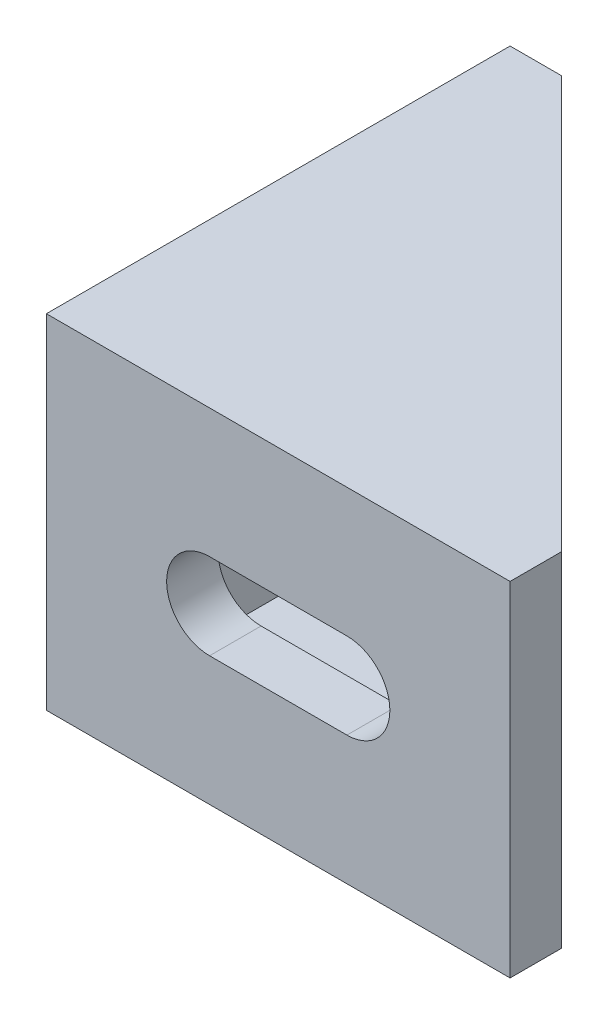
SolidWorks part; units mm, degrees
material "Gray Cast Iron"
ref_plane "Front Plane" through (0, 0, 0) normal (0, 0, 1) x (1, 0, 0)
ref_plane "Top Plane" through (0, 0, 0) normal (0, 1, 0) x (1, 0, 0)
ref_plane "Right Plane" through (0, 0, 0) normal (1, 0, 0) x (0, 0, -1)
sketch "Sketch1" plane through (0, 0, 0) normal (0, 0, 1) x (1, 0, 0)
  line L0 (4, 0) -> (-4, 0) construction
  line L1 (-13.5, 10) -> (13.5, 10)
  line L2 (-13.5, 10) -> (-13.5, -10)
  line L3 (-13.5, -10) -> (13.5, -10)
  line L4 (13.5, 10) -> (13.5, -10)
  line L5 (-13.5, 10) -> (13.5, -10) construction
  line L6 (-13.5, -10) -> (13.5, 10) construction
  line L7 (4, -2.5) -> (-4, -2.5)
  line L8 (4, 2.5) -> (-4, 2.5)
  arc A0 (4, -2.5) -> (4, 2.5) centre (4, 0) ccw
  arc A1 (-4, 2.5) -> (-4, -2.5) centre (-4, 0) ccw
  point P0 (0, 0)
  point P8 (4.0109, 1.5352)
  point P13 (0, 0)
  point P14 (4.0109, 0)
  point P15 (0, 0)
  point P16 (0, 0)
  point P17 (4, 2.5)
  dimension "D3" = 2.5
  dimension "D7" = 2.5
  dimension "D1" = 20
  dimension "D2" = 27
  dimension "D4" = 5
  dimension "D5" = 4
  dimension "D6" = 8
extrude "Boss-Extrude1" add sketch "Sketch1" along normal blind 3
sketch "Sketch2" plane through (0, 0, 0) normal (0, 0, -1) x (-1, 0, 0)
  line L0 (13.5, -10) -> (-13.5, -10) construction
  line L1 (13.5, 10) -> (10.5, 10)
  line L2 (13.5, 10) -> (13.5, -10)
  line L3 (13.5, -10) -> (10.5, -10)
  line L4 (10.5, 10) -> (10.5, -10)
  line L5 (12, -10) -> (12, 10) construction
  line L6 (13.5, 0) -> (10.5, 0) construction
  point P96 (12, 0)
  dimension "D1" = 3
extrude "Boss-Extrude2" add sketch "Sketch2" along normal blind 24
sketch "Sketch3" plane through (0, -10, 0) normal (0, -1, 0) x (1, 0, 0)
  line L0 (-10.5, -24) -> (13.5, 0)
  line L1 (13.5, 0) -> (13.5, 3)
  line L2 (13.5, 3) -> (-13.5, 3)
  line L3 (-13.5, 3) -> (-13.5, -24)
  line L4 (-13.5, -24) -> (-10.5, -24)
extrude "Boss-Extrude3" add sketch "Sketch3" against normal blind 2
mirror "Mirror1" about plane through (0, 0, 0) normal (0, 1, 0) of "Boss-Extrude3"
sketch "Sketch4" plane through (-10.5, 0, 0) normal (1, 0, 0) x (0, 0, -1)
  line L0 (12, 8) -> (12, -8) construction
  line L1 (0, 8) -> (24, 8) construction
  line L2 (24, -8) -> (0, -8) construction
  line L3 (0, 0) -> (24, 0) construction
  line L4 (0, 8) -> (0, -8) construction
  line L5 (24, 8) -> (24, -8) construction
  line L6 (8, 0) -> (16, 0) construction
  line L8 (8, 2.5) -> (16, 2.5)
  line L9 (8, -2.5) -> (16, -2.5)
  arc A0 (8, 2.5) -> (8, -2.5) centre (8, 0) ccw
  arc A1 (16, -2.5) -> (16, 2.5) centre (16, 0) ccw
  point P16 (12, 0)
extrude "Cut-Extrude1" cut sketch "Sketch4" against normal blind 3
